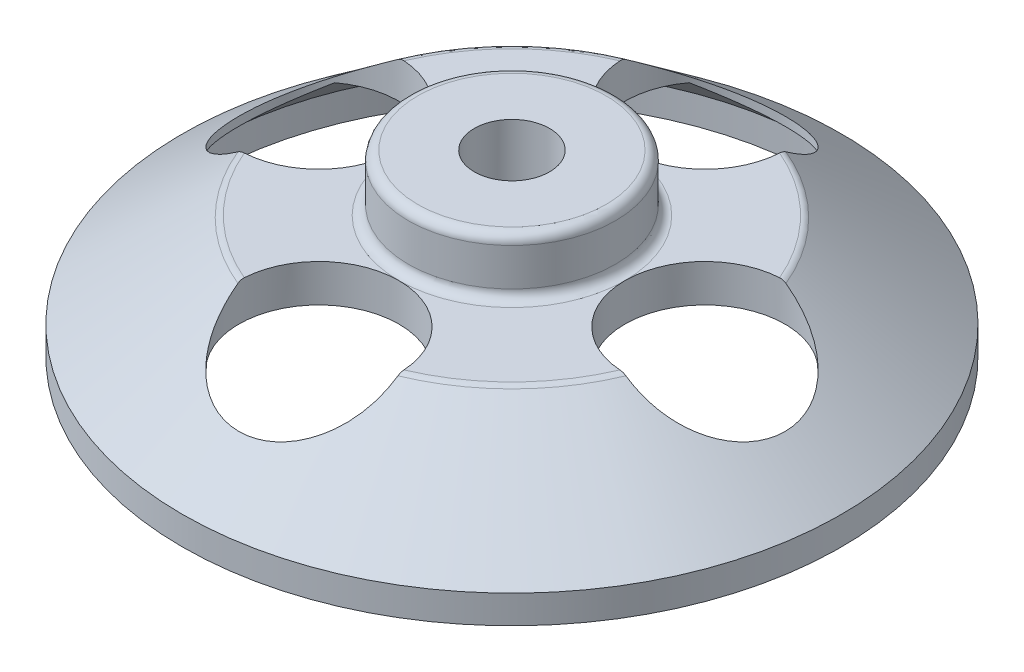
SolidWorks part; units mm, degrees
ref_plane "Front Plane" through (0, 0, 0) normal (0, 0, 1) x (1, 0, 0)
ref_plane "Top Plane" through (0, 0, 0) normal (0, 1, 0) x (1, 0, 0)
ref_plane "Right Plane" through (0, 0, 0) normal (1, 0, 0) x (0, 0, -1)
sketch "Sketch1" plane through (0, 0, 0) normal (0, 1, 0) x (1, 0, 0)
  circle A0 centre (0, 0) radius 17.5
  circle A1 centre (0, 0) radius 16.5
  dimension "D1" = 35
  dimension "D2" = 33
extrude "Boss-Extrude1" add sketch "Sketch1" along normal blind 1.5
sketch "Sketch2" plane through (0, 1.5, 0) normal (0, 1, 0) x (1, 0, 0)
  circle A1 centre (0, 0) radius 17.5
  circle A2 centre (0, 0) radius 17.5
  dimension "D1" = 0
extrude "Boss-Extrude2" add sketch "Sketch2" along normal blind 5 draft 52.4
sketch "Sketch3" plane through (0, 6.5, 0) normal (0, 1, 0) x (1, 0, 0)
  circle A1 centre (0, 0) radius 11.0074
  circle A2 centre (0, 0) radius 11.0074
  dimension "D2" = 22.0147
  dimension "D1" = 0
sketch "Sketch4" plane through (0, 1.5, 0) normal (0, -1, 0) x (1, 0, 0)
  circle A1 centre (0, 0) radius 16.5
  circle A2 centre (0, 0) radius 16.5
  dimension "D1" = 0
extrude "Cut-Extrude1" cut sketch "Sketch4" against normal blind 3 draft 47.3
sketch "Sketch5" plane through (0, 6.5, 0) normal (0, 1, 0) x (1, 0, 0)
  circle A0 centre (0, 0) radius 5.5
  dimension "D1" = 11
extrude "Boss-Extrude3" add sketch "Sketch5" along normal blind 3
fillet "Fillet1" radius 0.5 1 edges at (0, 9.5, 5.5)
sketch "Sketch6" plane through (0, 9.5, 0) normal (0, 1, 0) x (1, 0, 0)
  circle A0 centre (0, 0) radius 2
  dimension "D1" = 4
extrude "Cut-Extrude2" cut sketch "Sketch6" against normal through all
fillet "Fillet2" radius 0.5 1 edges at (0, 6.5, 5.5)
fillet "Fillet3" radius 0.5 1 edges at (0, 6.5, 11.0074)
sketch "Sketch7" plane through (0, 6.5, 0) normal (0, 1, 0) x (1, 0, 0)
  circle A0 centre (0, 10.25) radius 4.25
  circle A1 centre (0, 0) radius 6 construction
  circle A2 centre (10.25, 0) radius 4.25
  circle A3 centre (0, -10.25) radius 4.25
  circle A4 centre (-10.25, 0) radius 4.25
  point P12 (0, 0)
  dimension "D1" = 8.5
  dimension "D2" = 4
extrude "Cut-Extrude3" cut sketch "Sketch7" against normal through all
